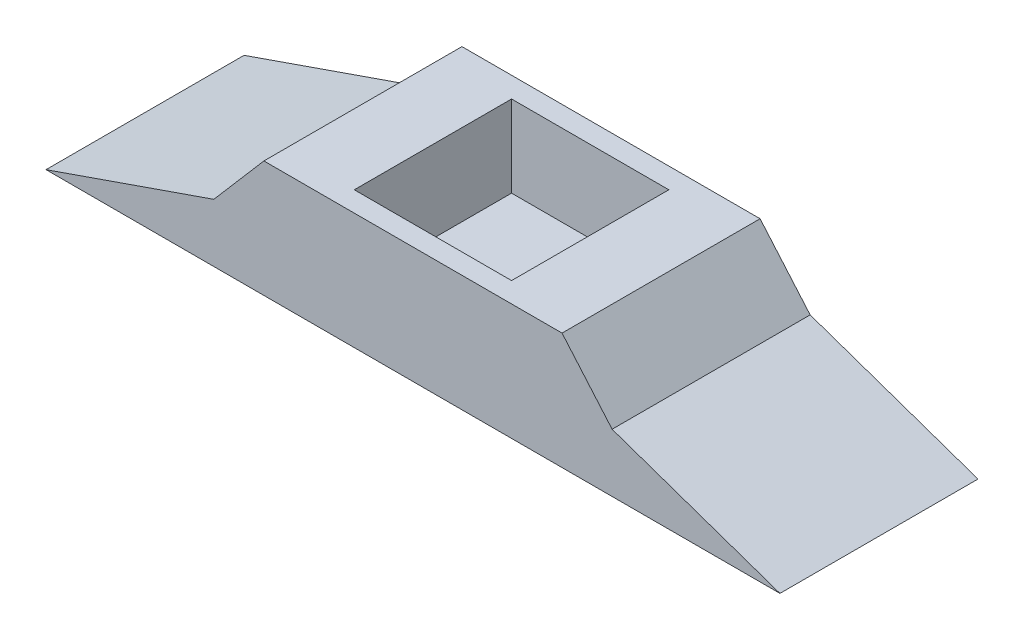
SolidWorks part; units mm, degrees
ref_plane "정면" through (0, 0, 0) normal (0, 0, 1) x (1, 0, 0)
ref_plane "윗면" through (0, 0, 0) normal (0, 1, 0) x (1, 0, 0)
ref_plane "우측면" through (0, 0, 0) normal (1, 0, 0) x (0, 0, -1)
sketch "스케치1" plane through (0, 0, 0) normal (0, 0, 1) x (1, 0, 0)
  line L0 (0, 0) -> (0, 1.9063) construction
  line L1 (-3.15, 0) -> (3.15, 0)
  line L2 (-3.15, 0) -> (-1.7093, 0.5)
  line L3 (3.15, 0) -> (1.7093, 0.5)
  line L4 (-1.7093, 0.5) -> (-1.2796, 1)
  line L5 (1.7093, 0.5) -> (1.2796, 1)
  line L6 (-1.2796, 1) -> (1.2796, 1)
  point P9 (0, 1)
  dimension "D1" = 6.3
  dimension "D2" = 0.5
  dimension "D3" = 0.5
  dimension "D4" = 2.5591
  dimension "D5" = 1.7093
extrude "보스-돌출2" add sketch "스케치1" along normal blind 1.7 contours L6 L5 L3 L1 L2 L4
sketch "스케치3" plane through (0, 1, 0) normal (0, 1, 0) x (1, 0, 0)
  line L0 (-1.2796, -0.85) -> (1.2796, -0.85) construction
  line L1 (-0.6772, -1.5265) -> (0.6728, -1.5265)
  line L2 (-0.6772, -1.5265) -> (-0.6772, -0.1765)
  line L3 (-0.6772, -0.1765) -> (0.6728, -0.1765)
  line L4 (0.6728, -1.5265) -> (0.6728, -0.1765)
  line L5 (-0.0022, -0.1765) -> (-0.0022, -1.5265) construction
  line L6 (-0.6772, -0.8515) -> (0.6728, -0.8515) construction
  line L7 (-1.2796, -1.7) -> (-1.2796, 0) construction
  line L8 (1.2796, -1.7) -> (1.2796, 0) construction
  line L9 (0, 0) -> (0, -1.7) construction
  line L10 (-1.2796, -1.7) -> (1.2796, -1.7) construction
  point P0 (-0.0022, -0.8515)
  dimension "D1" = 1.35
  dimension "D2" = 1.35
extrude "컷-돌출2" cut sketch "스케치3" against normal blind 1 from offset 0.3
scale "축척1" bodies to scale 104 scale about centroid uniform scaling yes scale factor 10
